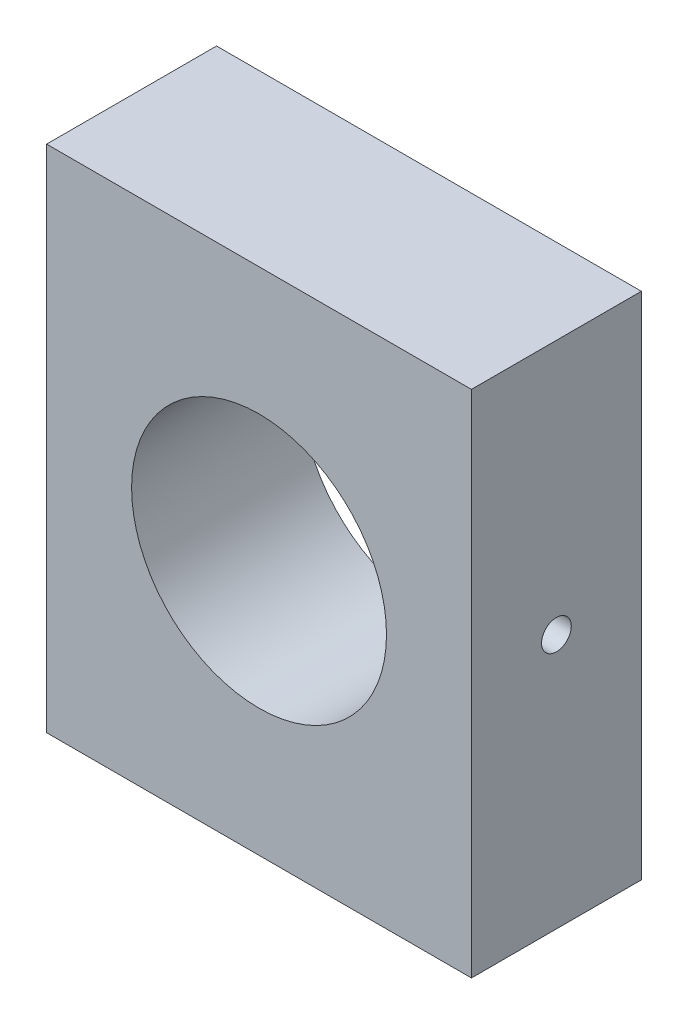
SolidWorks part; units mm, degrees
material "Teak"
ref_plane "Front Plane" through (0, 0, 0) normal (0, 0, 1) x (1, 0, 0)
ref_plane "Top Plane" through (0, 0, 0) normal (0, 1, 0) x (1, 0, 0)
ref_plane "Right Plane" through (0, 0, 0) normal (1, 0, 0) x (0, 0, -1)
sketch "Sketch1" plane through (0, 0, 0) normal (0, 0, 1) x (1, 0, 0)
  line L1 (-34.5135, 45.0602) -> (65.4865, 45.0602)
  line L2 (-34.5135, 45.0602) -> (-34.5135, -74.9398)
  line L3 (-34.5135, -74.9398) -> (65.4865, -74.9398)
  line L4 (65.4865, 45.0602) -> (65.4865, -74.9398)
  circle A0 centre (15.4865, -14.9398) radius 30
  dimension "D3" = 60
  dimension "D1" = 120
  dimension "D2" = 100
  dimension "D4" = 60
  dimension "D5" = 50
extrude "Boss-Extrude1" add sketch "Sketch1" along normal blind 40
sketch "Sketch2" plane through (-34.5135, 0, 0) normal (-1, 0, 0) x (0, 0, 1)
  line L0 (40, 45.0602) -> (0, 45.0602) construction
  line L1 (40, 45.0602) -> (40, -74.9398) construction
  circle A0 centre (20, -14.9398) radius 3.5
  dimension "D1" = 7
  dimension "D2" = 60
  dimension "D3" = 20
extrude "Cut-Extrude1" cut sketch "Sketch2" against normal blind 15
sketch "Sketch3" plane through (65.4865, 0, 0) normal (1, 0, 0) x (0, 0, -1)
  line L0 (-40, 45.0602) -> (0, 45.0602) construction
  line L1 (0, -74.9398) -> (0, 45.0602) construction
  circle A0 centre (-20, -14.9398) radius 3.5
  dimension "D1" = 7
  dimension "D2" = 60
  dimension "D3" = 20
extrude "Cut-Extrude2" cut sketch "Sketch3" against normal blind 15
